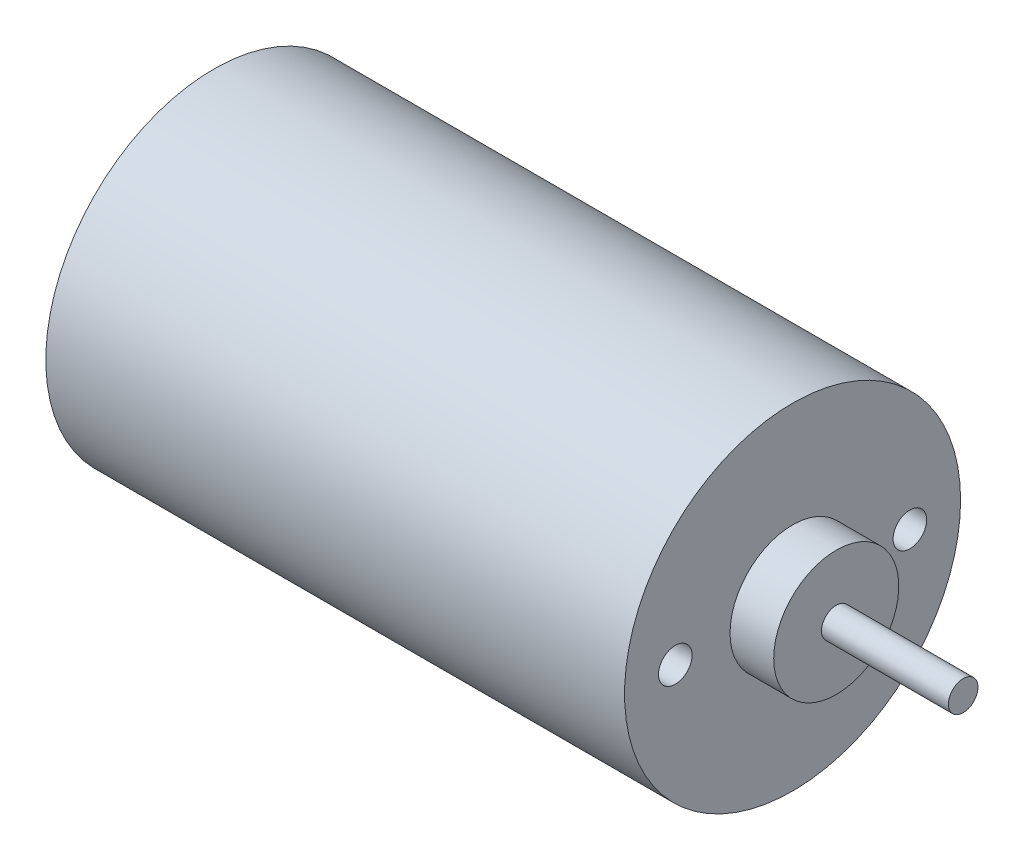
SolidWorks part; units mm, degrees
ref_plane "Front Plane" through (0, 0, 0) normal (0, 0, 1) x (1, 0, 0)
ref_plane "Top Plane" through (0, 0, 0) normal (0, 1, 0) x (1, 0, 0)
ref_plane "Right Plane" through (0, 0, 0) normal (1, 0, 0) x (0, 0, -1)
sketch "Sketch1" plane through (0, 0, 0) normal (1, 0, 0) x (0, 0, -1)
  circle A0 centre (0, 0) radius 18
  dimension "D1" = 36
extrude "Boss-Extrude1" add sketch "Sketch1" along normal blind 62
sketch "Sketch2" plane through (62, 0, 0) normal (1, 0, 0) x (0, 0, -1)
  circle A0 centre (0, 0) radius 6.7
  dimension "D1" = 13.4
extrude "Boss-Extrude2" add sketch "Sketch2" along normal blind 4.68
sketch "Sketch3" plane through (66.68, 0, 0) normal (1, 0, 0) x (0, 0, -1)
  circle A0 centre (0, 0) radius 1.585
  dimension "D1" = 3.17
extrude "Boss-Extrude3" add sketch "Sketch3" along normal blind 13.6
sketch "Sketch4" plane through (62, 0, 0) normal (1, 0, 0) x (0, 0, -1)
  line L0 (-12.565, 0) -> (12.565, 0) construction
  circle A0 centre (-12.565, 0) radius 1.8
  circle A1 centre (12.565, 0) radius 1.8
  point P6 (0, 0)
  dimension "D1" = 3.6
  dimension "D2" = 25.13
extrude "Cut-Extrude1" cut sketch "Sketch4" against normal blind 20
